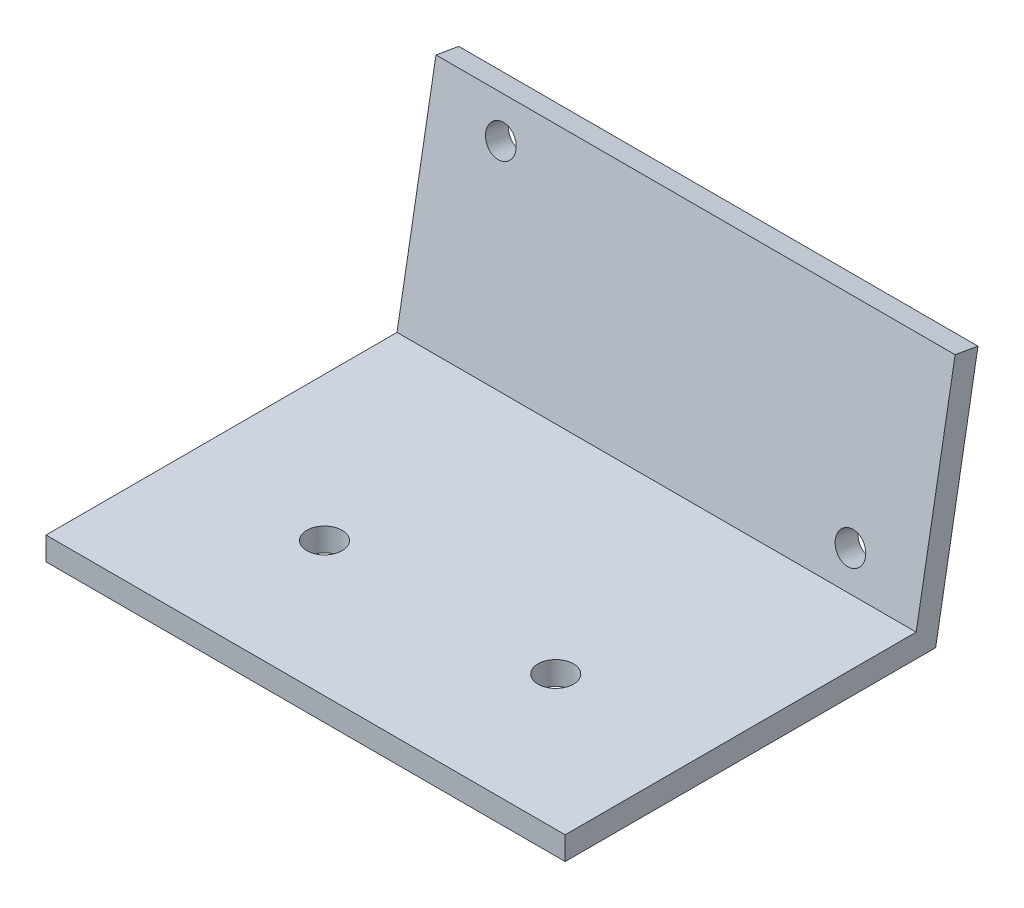
SolidWorks part; units mm, degrees
ref_plane "Front Plane" through (0, 0, 0) normal (0, 0, 1) x (1, 0, 0)
ref_plane "Top Plane" through (0, 0, 0) normal (0, 1, 0) x (1, 0, 0)
ref_plane "Right Plane" through (0, 0, 0) normal (1, 0, 0) x (0, 0, -1)
sketch "Sketch3" plane through (0, 0, 0) normal (1, 0, 0) x (0, 0, -1)
  line L0 (-72.719, -0.6612) -> (-72.719, 1.8388)
  line L1 (-72.719, 1.8388) -> (-34.9388, 1.8388)
  line L2 (-34.9388, 1.8388) -> (-30.7486, 25.6023)
  line L3 (-30.7486, 25.6023) -> (-28.2866, 25.1681)
  line L7 (-28.2866, 25.1681) -> (-32.841, -0.6612)
  line L8 (-32.841, -0.6612) -> (-72.719, -0.6612)
  dimension "D1" = 2.5
  dimension "D2" = 24.13
  dimension "D3" = 100
  dimension "D5" = 2.5
  dimension "D7" = 39.878
extrude "Boss-Extrude1" add sketch "Sketch3" against normal blind 55.88
sketch "Sketch4" plane through (0, 1.8388, 0) normal (0, 1, 0) x (1, 0, 0)
  circle A0 centre (-40.386, -58.241) radius 1.905
  circle A1 centre (-15.494, -58.241) radius 1.905
  dimension "D1" = 3.81
  dimension "D2" = 3.81
  dimension "D3" = 24.892
extrude "Cut-Extrude1" cut sketch "Sketch4" against normal blind 42.418
sketch "Sketch5" plane through (0, 5.5962, 31.7377) normal (0, -0.1736, -0.9848) x (-1, 0, 0)
  circle A0 centre (48.2149, 15.9633) radius 1.6256
  circle A1 centre (7.7216, -0.5467) radius 1.6256
  point P4 (48.2149, 15.9633)
  dimension "D1" = 3.2512
  dimension "D2" = 3.2512
  dimension "D4" = 16.51
extrude "Cut-Extrude2" cut sketch "Sketch5" against normal up to surface (2.5 mm away) up to face at (-27.94, 13.7205, 32.8437)
